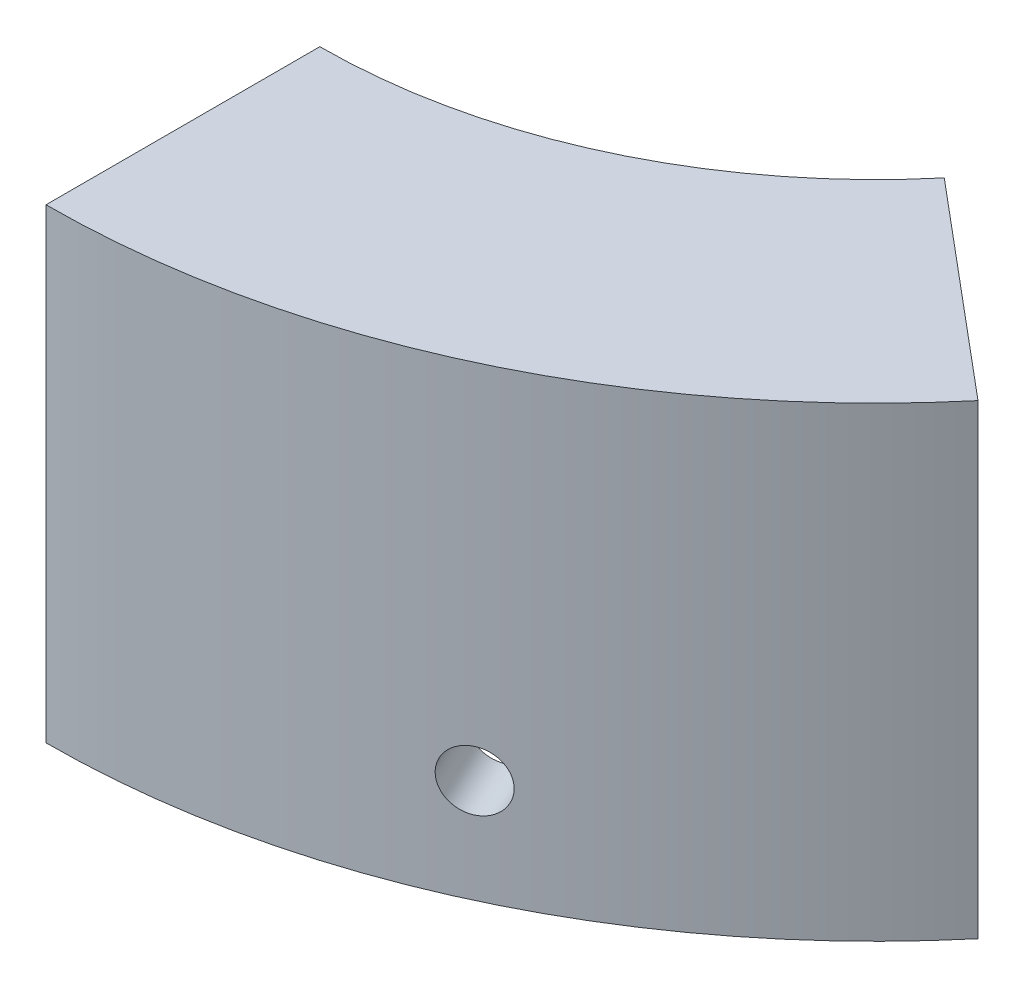
SolidWorks part; units mm, degrees
ref_plane "Front Plane" through (0, 0, 0) normal (0, 0, 1) x (1, 0, 0)
ref_plane "Top Plane" through (0, 0, 0) normal (0, 1, 0) x (1, 0, 0)
ref_plane "Right Plane" through (0, 0, 0) normal (1, 0, 0) x (0, 0, -1)
sketch "Sketch1" plane through (0, 0, 0) normal (0, 1, 0) x (1, 0, 0)
  line L0 (0, -43.2) -> (0, -46.8)
  line L1 (33.0931, -27.7684) -> (35.8509, -30.0825)
  circle A0 centre (0, 0) radius 46.8
  circle A1 centre (0, 0) radius 43.2
  dimension "D1" = 93.6
  dimension "D3" = 50
  dimension "D2" = 3.6
extrude "Boss-Extrude1" add sketch "Sketch1" along normal blind 6.25 contours A1 L0 A0 L1
sketch "Sketch2" plane through (0, 6.25, 0) normal (0, 1, 0) x (1, 0, 0)
  line L0 (0, -40.2) -> (0, -60)
  line L1 (45.9627, -38.5673) -> (30.795, -25.8401)
  line L2 (33.0931, -27.7684) -> (35.8509, -30.0825) construction
  circle A0 centre (0, 0) radius 60
  circle A1 centre (0, 0) radius 40.2
  arc M4 (33.0931, -27.7684) -> (0, -43.2) centre (0, 0) cw
  line M5 (0, -43.2) -> (0, -46.8)
  arc M6 (0, -46.8) -> (35.8509, -30.0825) centre (0, 0) ccw
  line M7 (35.8509, -30.0825) -> (33.0931, -27.7684)
  dimension "D1" = 120
  dimension "D2" = 80.4
extrude "Boss-Extrude2" add sketch "Sketch2" along normal blind 5 contours L0 A0 L1 M6 | M7 M4 M5 M6 | A1 L0 L1 M4
sketch "Sketch3" plane through (0, 6.25, 0) normal (0, -1, 0) x (-1, 0, 0)
  arc A2 (-42.2857, -35.4819) -> (0, -55.2) centre (0, 0) ccw
  arc A3 (-42.2857, -35.4819) -> (0, -55.2) centre (0, 0) ccw
  line M2 (0, -60) -> (0, -46.8)
  line M4 (-35.8509, -30.0825) -> (-45.9627, -38.5673)
  arc M5 (-45.9627, -38.5673) -> (0, -60) centre (0, 0) ccw
  dimension "D1" = 4.8
extrude "Boss-Extrude3" add sketch "Sketch3" along normal blind 28.7 contours A3 M4 M5 M2
ref_plane "Plane1" through (15.3975, 0, 33.02) normal (0.4226, 0, 0.9063) x (0.9063, 0, -0.4226)
sketch "Sketch4" plane through (15.3975, 0, 33.02) normal (0.4226, 0, 0.9063) x (0.9063, 0, -0.4226)
  line L0 (-25.3571, -22.45) -> (25.3571, -22.45) construction
  circle A0 centre (0, -14.95) radius 2.15
  point P4 (0, 0)
  dimension "D1" = 4.3
  dimension "D2" = 7.5
extrude "M4-through hole" cut sketch "Sketch4" along normal through all
